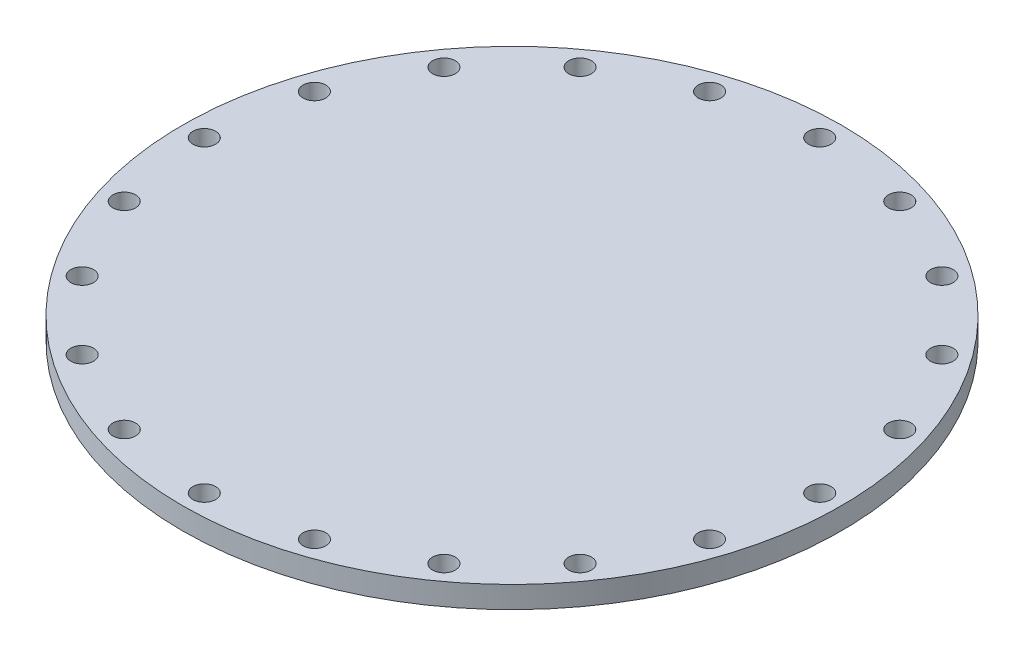
SolidWorks part; units mm, degrees
ref_plane "Front Plane" through (0, 0, 0) normal (0, 0, 1) x (1, 0, 0)
ref_plane "Top Plane" through (0, 0, 0) normal (0, 1, 0) x (1, 0, 0)
ref_plane "Right Plane" through (0, 0, 0) normal (1, 0, 0) x (0, 0, -1)
sketch "Sketch1" plane through (0, 0, 0) normal (0, 1, 0) x (1, 0, 0)
  line L0 (0, 243.1561) -> (0, -112.1888) construction
  line L1 (-166.393, 0) -> (134.9755, 0) construction
  circle A0 centre (0, 0) radius 377.5
  circle A1 centre (0, 0) radius 352.5 construction
  circle A2 centre (0, 352.5) radius 13
  circle A3 centre (108.9285, 335.2474) radius 13
  circle A4 centre (207.1943, 285.1785) radius 13
  circle A5 centre (285.1785, 207.1943) radius 13
  circle A6 centre (335.2474, 108.9285) radius 13
  circle A7 centre (352.5, 0) radius 13
  circle A8 centre (335.2474, -108.9285) radius 13
  circle A9 centre (285.1785, -207.1943) radius 13
  circle A10 centre (207.1943, -285.1785) radius 13
  circle A11 centre (108.9285, -335.2474) radius 13
  circle A12 centre (0, -352.5) radius 13
  circle A13 centre (-108.9285, -335.2474) radius 13
  circle A14 centre (-207.1943, -285.1785) radius 13
  circle A15 centre (-285.1785, -207.1943) radius 13
  circle A16 centre (-335.2474, -108.9285) radius 13
  circle A17 centre (-352.5, 0) radius 13
  circle A18 centre (-335.2474, 108.9285) radius 13
  circle A19 centre (-285.1785, 207.1943) radius 13
  circle A20 centre (-207.1943, 285.1785) radius 13
  circle A21 centre (-108.9285, 335.2474) radius 13
  point P51 (0, 0)
  dimension "D1" = 755
  dimension "D2" = 705
  dimension "D3" = 26
  dimension "D4" = 20
extrude "Boss-Extrude1" add sketch "Sketch1" along normal mid plane 25
